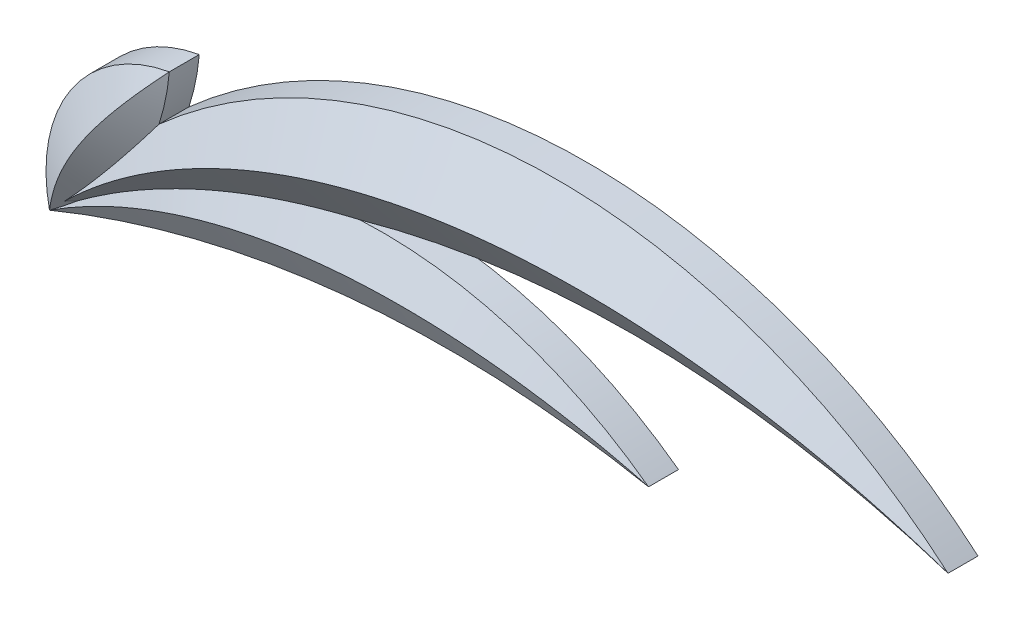
SolidWorks part; units mm, degrees
ref_plane "Plano frontal" through (0, 0, 0) normal (0, 0, 1) x (1, 0, 0)
ref_plane "Plano superior" through (0, 0, 0) normal (0, 1, 0) x (1, 0, 0)
ref_plane "Plano direito" through (0, 0, 0) normal (1, 0, 0) x (0, 0, -1)
sketch "Esboço1" plane through (0, 0, 0) normal (0, 0, 1) x (1, 0, 0)
  spline S0 degree 2 poles (0, 0) (18.1517, 12.2016) (40, 4) knots 0 0 0 1 1 1 construction
  spline S2 degree 2 poles (0, 0) (1.9597, 7.2357) (8, 12) knots 0 0 0 1 1 1 construction
  spline S3 degree 3 poles (0, 0) (13.7782, 18.1009) (41.168, 18.842) (60, 9) knots 0 0 0 0 1 1 1 1 construction
  dimension "D2" = 4
  dimension "D3" = 12
  dimension "D4" = 40
  dimension "D5" = 6
  dimension "D6" = 13
  dimension "D7" = 9
  dimension "D8" = 13
  dimension "D9" = 8
  dimension "D10" = 2
  dimension "D11" = 5
  dimension "D12" = 12
  dimension "D13" = 16
  dimension "D14" = 50
  dimension "D15" = 60
sketch "Esboço4" plane through (0, 0, 0) normal (0, 0, 1) x (1, 0, 0)
  arc A6 (0, 0) -> (8, 12) centre (9.7646, 2.1569) cw
  arc A7 (0, 0) -> (8, 12) centre (-6.9439, 13.2959) ccw
  arc A8 (0, 0) -> (60, 9) centre (33.8675, -21.2836) cw
  arc A9 (0, 0) -> (60, 9) centre (39.0278, -55.6851) cw
  arc A10 (0, 0) -> (40, 4) centre (22.2161, -20.1605) cw
  arc A11 (0, 0) -> (40, 4) centre (26.6719, -64.7195) cw
  dimension "D1" = 10
  dimension "D2" = 15
  dimension "D3" = 40
  dimension "D4" = 68
  dimension "D5" = 30
  dimension "D6" = 70
sketch "Esboço5" plane through (0, 0, 0) normal (0, 0, 1) x (1, 0, 0)
  arc A0 (0, 0) -> (8, 12) centre (9.7646, 2.1569) cw
  arc A1 (0, 0) -> (8, 12) centre (-6.9439, 13.2959) ccw
  arc A4 (8, 12) -> (0, 0) centre (9.7646, 2.1569) ccw construction
  arc A5 (0, 0) -> (8, 12) centre (-6.9439, 13.2959) ccw construction
extrude "Ressalto-extrusão1" add sketch "Esboço5" along normal blind 15 draft 60
sketch "Esboço6" plane through (0, 0, 0) normal (0, 0, 1) x (1, 0, 0)
  arc A0 (0, 0) -> (60, 9) centre (33.8675, -21.2836) cw
  arc A1 (0, 0) -> (60, 9) centre (39.0278, -55.6851) cw
  arc A4 (60, 9) -> (0, 0) centre (33.8675, -21.2836) ccw construction
  arc A5 (60, 9) -> (0, 0) centre (39.0278, -55.6851) ccw construction
extrude "Ressalto-extrusão2" add sketch "Esboço6" along normal blind 5 draft 53
sketch "Esboço7" plane through (0, 0, 0) normal (0, 0, 1) x (1, 0, 0)
  arc A0 (0, 0) -> (40, 4) centre (22.2161, -20.1605) cw
  arc A1 (0, 0) -> (40, 4) centre (26.6719, -64.7195) cw
  arc A4 (40, 4) -> (0, 0) centre (22.2161, -20.1605) ccw construction
  arc A5 (40, 4) -> (0, 0) centre (26.6719, -64.7195) ccw construction
extrude "Ressalto-extrusão3" add sketch "Esboço7" along normal blind 5 draft 60
sketch "Esboço8" plane through (0, 0, 0) normal (0, 0, 1) x (1, 0, 0)
  arc A0 (0, 0) -> (8, 12) centre (9.7646, 2.1569) cw
  arc A3 (8, 12) -> (7.3118, 8.6295) centre (-6.9439, 13.2959) cw
  arc A4 (7.3118, 8.6295) -> (60, 9) centre (33.8675, -21.2836) cw
  arc A6 (60, 9) -> (20.7119, 9.8017) centre (39.0278, -55.6851) ccw
  arc A8 (20.7119, 9.8017) -> (40, 4) centre (22.2161, -20.1605) cw
  arc A10 (40, 4) -> (0, 0) centre (26.6719, -64.7195) ccw
  arc A12 (8, 12) -> (0, 0) centre (9.7646, 2.1569) ccw construction
  arc A13 (7.3118, 8.6295) -> (8, 12) centre (-6.9439, 13.2959) ccw construction
  arc A14 (60, 9) -> (7.3118, 8.6295) centre (33.8675, -21.2836) ccw construction
  arc A15 (60, 9) -> (20.7119, 9.8017) centre (39.0278, -55.6851) ccw construction
  arc A16 (40, 4) -> (20.7119, 9.8017) centre (22.2161, -20.1605) ccw construction
  arc A17 (40, 4) -> (0, 0) centre (26.6719, -64.7195) ccw construction
extrude "Ressalto-extrusão4" add sketch "Esboço8" against normal blind 2
